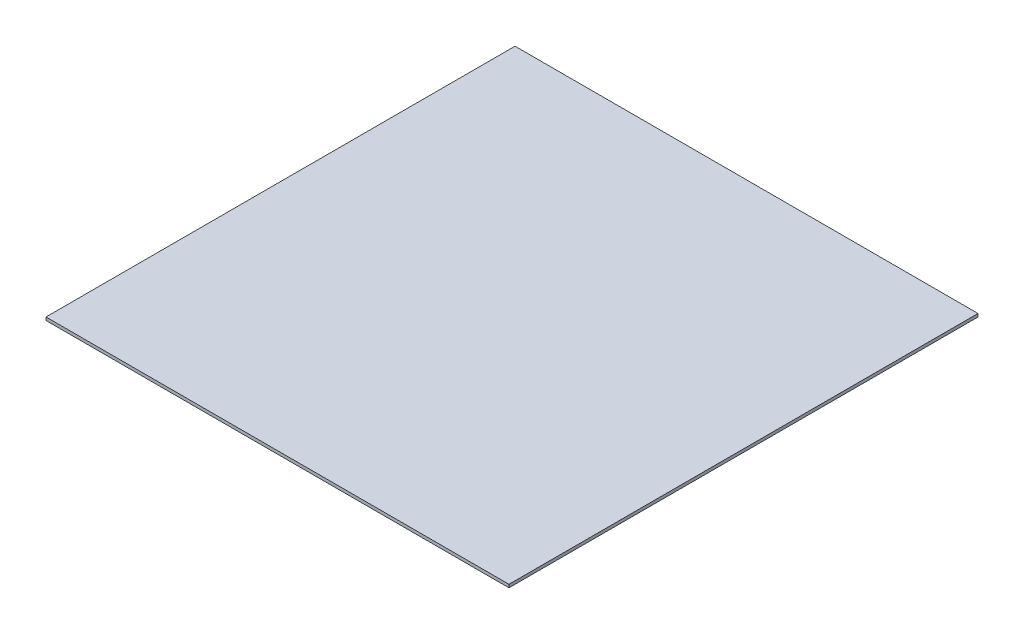
SolidWorks part; units mm, degrees
ref_plane "Front Plane" through (0, 0, 0) normal (0, 0, 1) x (1, 0, 0)
ref_plane "Top Plane" through (0, 0, 0) normal (0, 1, 0) x (1, 0, 0)
ref_plane "Right Plane" through (0, 0, 0) normal (1, 0, 0) x (0, 0, -1)
sketch "Sketch1" plane through (0, 0, 0) normal (0, 1, 0) x (1, 0, 0)
  line L1 (-225.65, 228.6) -> (225.65, 228.6)
  line L2 (-225.65, 228.6) -> (-225.65, -228.6)
  line L3 (-225.65, -228.6) -> (225.65, -228.6)
  line L4 (225.65, 228.6) -> (225.65, -228.6)
  line L5 (-225.65, 228.6) -> (225.65, -228.6) construction
  line L6 (-225.65, -228.6) -> (225.65, 228.6) construction
  point P0 (0, 0)
  dimension "D1" = 457.2
  dimension "D2" = 451.3
extrude "Boss-Extrude1" add sketch "Sketch1" along normal blind 3
